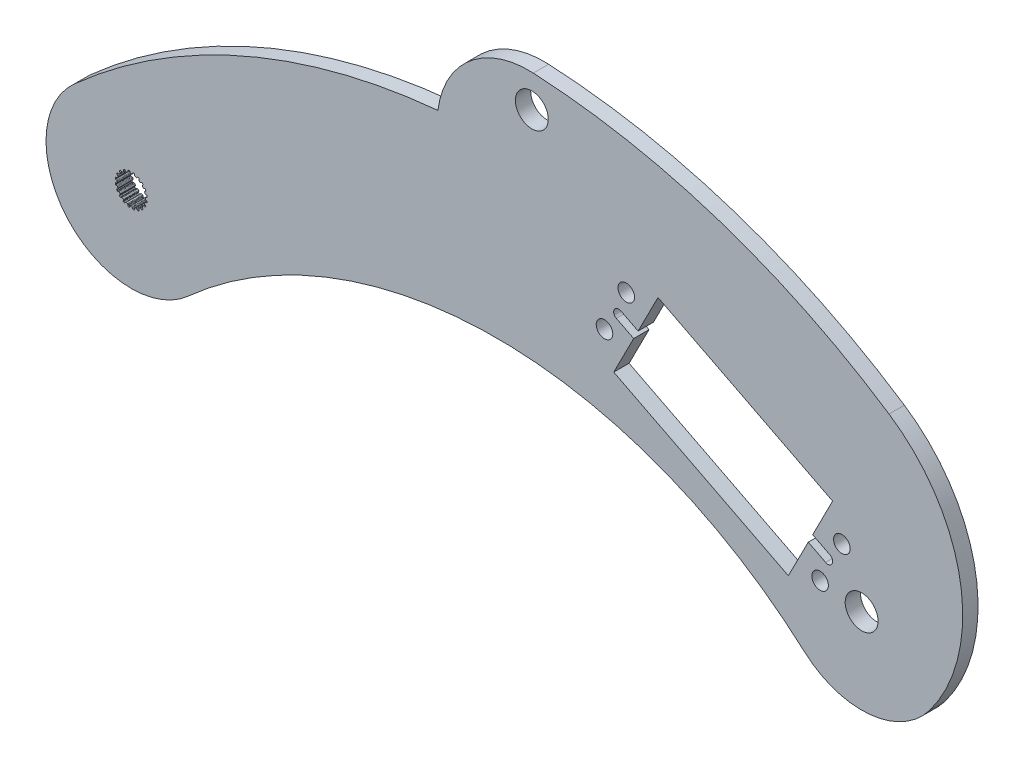
SolidWorks part; units mm, degrees
ref_plane "Front Plane" through (0, 0, 0) normal (0, 0, 1) x (1, 0, 0)
ref_plane "Top Plane" through (0, 0, 0) normal (0, 1, 0) x (1, 0, 0)
ref_plane "Right Plane" through (0, 0, 0) normal (1, 0, 0) x (0, 0, -1)
sketch "Sketch1" plane through (0, 0, 0) normal (0, 0, 1) x (1, 0, 0)
  line L0 (-0.1069, 2.9699) -> (0.1069, 2.9699)
  line L1 (0.3159, 3.2375) -> (0.2537, 3.0575)
  line L2 (-0.2964, 3.2367) -> (-0.2318, 3.0575)
  line L3 (-0.2964, 3.2367) -> (0.3159, 3.2375) construction
  line L4 (0, 3.3252) -> (0, 0) construction
  line L5 (-0.2318, 3.0575) -> (0.2537, 3.0575) construction
  line L6 (-0.4281, 3.3241) -> (0.4281, 3.3263) construction
  line L7 (0.7183, 3.1698) -> (0.7244, 2.9795)
  line L8 (0.816, 2.8576) -> (1.0195, 2.7915)
  line L9 (1.3009, 2.9815) -> (1.1862, 2.8295)
  line L10 (1.6627, 2.7927) -> (1.6097, 2.6099)
  line L11 (1.6591, 2.4655) -> (1.8322, 2.3398)
  line L12 (2.1585, 2.4335) -> (2.0025, 2.3245)
  line L13 (2.4443, 2.1423) -> (2.3374, 1.9847)
  line L14 (2.3398, 1.8322) -> (2.4655, 1.6591)
  line L15 (2.8049, 1.6474) -> (2.6228, 1.5919)
  line L16 (2.9866, 1.2821) -> (2.8363, 1.1653)
  line L17 (2.7915, 1.0195) -> (2.8576, 0.816)
  line L18 (3.1767, 0.7) -> (2.9863, 0.7035)
  line L19 (3.2367, 0.2964) -> (3.0575, 0.2318)
  line L20 (2.9699, 0.1069) -> (2.9699, -0.1069)
  line L21 (3.2375, -0.3159) -> (3.0575, -0.2537)
  line L22 (3.1698, -0.7183) -> (2.9795, -0.7244)
  line L23 (2.8576, -0.816) -> (2.7915, -1.0195)
  line L24 (2.9815, -1.3009) -> (2.8295, -1.1862)
  line L25 (2.7927, -1.6627) -> (2.6099, -1.6097)
  line L26 (2.4655, -1.6591) -> (2.3398, -1.8322)
  line L27 (2.4335, -2.1585) -> (2.3245, -2.0025)
  line L28 (2.1423, -2.4443) -> (1.9847, -2.3374)
  line L29 (1.8322, -2.3398) -> (1.6591, -2.4655)
  line L30 (1.6474, -2.8049) -> (1.5919, -2.6228)
  line L31 (1.2821, -2.9866) -> (1.1653, -2.8363)
  line L32 (1.0195, -2.7915) -> (0.816, -2.8576)
  line L33 (0.7, -3.1767) -> (0.7035, -2.9863)
  line L34 (0.2964, -3.2367) -> (0.2318, -3.0575)
  line L35 (0.1069, -2.9699) -> (-0.1069, -2.9699)
  line L36 (-0.3159, -3.2375) -> (-0.2537, -3.0575)
  line L37 (-0.7183, -3.1698) -> (-0.7244, -2.9795)
  line L38 (-0.816, -2.8576) -> (-1.0195, -2.7915)
  line L39 (-1.3009, -2.9815) -> (-1.1862, -2.8295)
  line L40 (-1.6627, -2.7927) -> (-1.6097, -2.6099)
  line L41 (-1.6591, -2.4655) -> (-1.8322, -2.3398)
  line L42 (-2.1585, -2.4335) -> (-2.0025, -2.3245)
  line L43 (-2.4443, -2.1423) -> (-2.3374, -1.9847)
  line L44 (-2.3398, -1.8322) -> (-2.4655, -1.6591)
  line L45 (-2.8049, -1.6474) -> (-2.6228, -1.5919)
  line L46 (-2.9866, -1.2821) -> (-2.8363, -1.1653)
  line L47 (-2.7915, -1.0195) -> (-2.8576, -0.816)
  line L48 (-3.1767, -0.7) -> (-2.9863, -0.7035)
  line L49 (-3.2367, -0.2964) -> (-3.0575, -0.2318)
  line L50 (-2.9699, -0.1069) -> (-2.9699, 0.1069)
  line L51 (-3.2375, 0.3159) -> (-3.0575, 0.2537)
  line L52 (-3.1698, 0.7183) -> (-2.9795, 0.7244)
  line L53 (-2.8576, 0.816) -> (-2.7915, 1.0195)
  line L54 (-2.9815, 1.3009) -> (-2.8295, 1.1862)
  line L55 (-2.7927, 1.6627) -> (-2.6099, 1.6097)
  line L56 (-2.4655, 1.6591) -> (-2.3398, 1.8322)
  line L57 (-2.4335, 2.1585) -> (-2.3245, 2.0025)
  line L58 (-2.1423, 2.4443) -> (-1.9847, 2.3374)
  line L59 (-1.8322, 2.3398) -> (-1.6591, 2.4655)
  line L60 (-1.6474, 2.8049) -> (-1.5919, 2.6228)
  line L61 (-1.2821, 2.9866) -> (-1.1653, 2.8363)
  line L62 (-1.0195, 2.7915) -> (-0.816, 2.8576)
  line L63 (-0.7, 3.1767) -> (-0.7035, 2.9863)
  line L64 (0.4281, 3.3263) -> (0.62, 3.2938)
  line L65 (1.4351, 3.0312) -> (1.6075, 2.9409)
  line L66 (2.3015, 2.4394) -> (2.4376, 2.3003)
  line L67 (2.9427, 1.6088) -> (3.0291, 1.4344)
  line L68 (3.2958, 0.6207) -> (3.3241, 0.4281)
  line L69 (3.3263, -0.4281) -> (3.2938, -0.62)
  line L70 (3.0312, -1.4351) -> (2.9409, -1.6075)
  line L71 (2.4394, -2.3015) -> (2.3003, -2.4376)
  line L72 (1.6088, -2.9427) -> (1.4344, -3.0291)
  line L73 (0.6207, -3.2958) -> (0.4281, -3.3241)
  line L74 (-0.4281, -3.3263) -> (-0.62, -3.2938)
  line L75 (-1.4351, -3.0312) -> (-1.6075, -2.9409)
  line L76 (-2.3015, -2.4394) -> (-2.4376, -2.3003)
  line L77 (-2.9427, -1.6088) -> (-3.0291, -1.4344)
  line L78 (-3.2958, -0.6207) -> (-3.3241, -0.4281)
  line L79 (-3.3263, 0.4281) -> (-3.2938, 0.62)
  line L80 (-3.0312, 1.4351) -> (-2.9409, 1.6075)
  line L81 (-2.4394, 2.3015) -> (-2.3003, 2.4376)
  line L82 (-1.6088, 2.9427) -> (-1.4344, 3.0291)
  line L83 (-0.6207, 3.2958) -> (-0.4281, 3.3241)
  line L84 (-11.8753, 13.2369) -> (11.8753, -13.2369) construction
  line L85 (164.2753, 13.2369) -> (140.5247, -13.2369) construction
  line L86 (0, 0) -> (152.4, 0) construction
  arc A0 (0.2537, 3.0575) -> (0.1069, 2.9699) centre (0.1283, 3.1009) cw
  arc A1 (-0.2318, 3.0575) -> (-0.1069, 2.9699) centre (-0.1069, 3.1026) ccw
  arc A2 (0.62, 3.2938) -> (0.7183, 3.1698) centre (0.5856, 3.1656) cw
  arc A3 (0.7244, 2.9795) -> (0.816, 2.8576) centre (0.857, 2.9838) ccw
  arc A4 (-0.4281, 3.3241) -> (-0.2964, 3.2367) centre (-0.4213, 3.1916) cw
  arc A5 (0.4281, 3.3263) -> (0.3159, 3.2375) centre (0.4413, 3.1942) ccw
  arc A6 (1.1862, 2.8295) -> (1.0195, 2.7915) centre (1.0802, 2.9095) cw
  arc A7 (1.4351, 3.0312) -> (1.3009, 2.9815) centre (1.4068, 2.9015) ccw
  arc A8 (1.6075, 2.9409) -> (1.6627, 2.7927) centre (1.5352, 2.8297) cw
  arc A9 (1.6097, 2.6099) -> (1.6591, 2.4655) centre (1.7371, 2.5729) ccw
  arc A10 (2.0025, 2.3245) -> (1.8322, 2.3398) centre (1.9264, 2.4332) cw
  arc A11 (2.3015, 2.4394) -> (2.1585, 2.4335) centre (2.2346, 2.3248) ccw
  arc A12 (2.4376, 2.3003) -> (2.4443, 2.1423) centre (2.3345, 2.2168) cw
  arc A13 (2.3374, 1.9847) -> (2.3398, 1.8322) centre (2.4472, 1.9102) ccw
  arc A14 (2.6228, 1.5919) -> (2.4655, 1.6591) centre (2.5841, 1.7189) cw
  arc A15 (2.9427, 1.6088) -> (2.8049, 1.6474) centre (2.8436, 1.5205) ccw
  arc A16 (3.0291, 1.4344) -> (2.9866, 1.2821) centre (2.9052, 1.3869) cw
  arc A17 (2.8363, 1.1653) -> (2.7915, 1.0195) centre (2.9177, 1.0605) ccw
  arc A18 (2.9863, 0.7035) -> (2.8576, 0.816) centre (2.9887, 0.8362) cw
  arc A19 (3.2958, 0.6207) -> (3.1767, 0.7) centre (3.1743, 0.5673) ccw
  arc A20 (3.3241, 0.4281) -> (3.2367, 0.2964) centre (3.1916, 0.4213) cw
  arc A21 (3.0575, 0.2318) -> (2.9699, 0.1069) centre (3.1026, 0.1069) ccw
  arc A22 (3.0575, -0.2537) -> (2.9699, -0.1069) centre (3.1009, -0.1283) cw
  arc A23 (3.3263, -0.4281) -> (3.2375, -0.3159) centre (3.1942, -0.4413) ccw
  arc A24 (3.2938, -0.62) -> (3.1698, -0.7183) centre (3.1656, -0.5856) cw
  arc A25 (2.9795, -0.7244) -> (2.8576, -0.816) centre (2.9838, -0.857) ccw
  arc A26 (2.8295, -1.1862) -> (2.7915, -1.0195) centre (2.9095, -1.0802) cw
  arc A27 (3.0312, -1.4351) -> (2.9815, -1.3009) centre (2.9015, -1.4068) ccw
  arc A28 (2.9409, -1.6075) -> (2.7927, -1.6627) centre (2.8297, -1.5352) cw
  arc A29 (2.6099, -1.6097) -> (2.4655, -1.6591) centre (2.5729, -1.7371) ccw
  arc A30 (2.3245, -2.0025) -> (2.3398, -1.8322) centre (2.4332, -1.9264) cw
  arc A31 (2.4394, -2.3015) -> (2.4335, -2.1585) centre (2.3248, -2.2346) ccw
  arc A32 (2.3003, -2.4376) -> (2.1423, -2.4443) centre (2.2168, -2.3345) cw
  arc A33 (1.9847, -2.3374) -> (1.8322, -2.3398) centre (1.9102, -2.4472) ccw
  arc A34 (1.5919, -2.6228) -> (1.6591, -2.4655) centre (1.7189, -2.5841) cw
  arc A35 (1.6088, -2.9427) -> (1.6474, -2.8049) centre (1.5205, -2.8436) ccw
  arc A36 (1.4344, -3.0291) -> (1.2821, -2.9866) centre (1.3869, -2.9052) cw
  arc A37 (1.1653, -2.8363) -> (1.0195, -2.7915) centre (1.0605, -2.9177) ccw
  arc A38 (0.7035, -2.9863) -> (0.816, -2.8576) centre (0.8362, -2.9887) cw
  arc A39 (0.6207, -3.2958) -> (0.7, -3.1767) centre (0.5673, -3.1743) ccw
  arc A40 (0.4281, -3.3241) -> (0.2964, -3.2367) centre (0.4213, -3.1916) cw
  arc A41 (0.2318, -3.0575) -> (0.1069, -2.9699) centre (0.1069, -3.1026) ccw
  arc A42 (-0.2537, -3.0575) -> (-0.1069, -2.9699) centre (-0.1283, -3.1009) cw
  arc A43 (-0.4281, -3.3263) -> (-0.3159, -3.2375) centre (-0.4413, -3.1942) ccw
  arc A44 (-0.62, -3.2938) -> (-0.7183, -3.1698) centre (-0.5856, -3.1656) cw
  arc A45 (-0.7244, -2.9795) -> (-0.816, -2.8576) centre (-0.857, -2.9838) ccw
  arc A46 (-1.1862, -2.8295) -> (-1.0195, -2.7915) centre (-1.0802, -2.9095) cw
  arc A47 (-1.4351, -3.0312) -> (-1.3009, -2.9815) centre (-1.4068, -2.9015) ccw
  arc A48 (-1.6075, -2.9409) -> (-1.6627, -2.7927) centre (-1.5352, -2.8297) cw
  arc A49 (-1.6097, -2.6099) -> (-1.6591, -2.4655) centre (-1.7371, -2.5729) ccw
  arc A50 (-2.0025, -2.3245) -> (-1.8322, -2.3398) centre (-1.9264, -2.4332) cw
  arc A51 (-2.3015, -2.4394) -> (-2.1585, -2.4335) centre (-2.2346, -2.3248) ccw
  arc A52 (-2.4376, -2.3003) -> (-2.4443, -2.1423) centre (-2.3345, -2.2168) cw
  arc A53 (-2.3374, -1.9847) -> (-2.3398, -1.8322) centre (-2.4472, -1.9102) ccw
  arc A54 (-2.6228, -1.5919) -> (-2.4655, -1.6591) centre (-2.5841, -1.7189) cw
  arc A55 (-2.9427, -1.6088) -> (-2.8049, -1.6474) centre (-2.8436, -1.5205) ccw
  arc A56 (-3.0291, -1.4344) -> (-2.9866, -1.2821) centre (-2.9052, -1.3869) cw
  arc A57 (-2.8363, -1.1653) -> (-2.7915, -1.0195) centre (-2.9177, -1.0605) ccw
  arc A58 (-2.9863, -0.7035) -> (-2.8576, -0.816) centre (-2.9887, -0.8362) cw
  arc A59 (-3.2958, -0.6207) -> (-3.1767, -0.7) centre (-3.1743, -0.5673) ccw
  arc A60 (-3.3241, -0.4281) -> (-3.2367, -0.2964) centre (-3.1916, -0.4213) cw
  arc A61 (-3.0575, -0.2318) -> (-2.9699, -0.1069) centre (-3.1026, -0.1069) ccw
  arc A62 (-3.0575, 0.2537) -> (-2.9699, 0.1069) centre (-3.1009, 0.1283) cw
  arc A63 (-3.3263, 0.4281) -> (-3.2375, 0.3159) centre (-3.1942, 0.4413) ccw
  arc A64 (-3.2938, 0.62) -> (-3.1698, 0.7183) centre (-3.1656, 0.5856) cw
  arc A65 (-2.9795, 0.7244) -> (-2.8576, 0.816) centre (-2.9838, 0.857) ccw
  arc A66 (-2.8295, 1.1862) -> (-2.7915, 1.0195) centre (-2.9095, 1.0802) cw
  arc A67 (-3.0312, 1.4351) -> (-2.9815, 1.3009) centre (-2.9015, 1.4068) ccw
  arc A68 (-2.9409, 1.6075) -> (-2.7927, 1.6627) centre (-2.8297, 1.5352) cw
  arc A69 (-2.6099, 1.6097) -> (-2.4655, 1.6591) centre (-2.5729, 1.7371) ccw
  arc A70 (-2.3245, 2.0025) -> (-2.3398, 1.8322) centre (-2.4332, 1.9264) cw
  arc A71 (-2.4394, 2.3015) -> (-2.4335, 2.1585) centre (-2.3248, 2.2346) ccw
  arc A72 (-2.3003, 2.4376) -> (-2.1423, 2.4443) centre (-2.2168, 2.3345) cw
  arc A73 (-1.9847, 2.3374) -> (-1.8322, 2.3398) centre (-1.9102, 2.4472) ccw
  arc A74 (-1.5919, 2.6228) -> (-1.6591, 2.4655) centre (-1.7189, 2.5841) cw
  arc A75 (-1.6088, 2.9427) -> (-1.6474, 2.8049) centre (-1.5205, 2.8436) ccw
  arc A76 (-1.4344, 3.0291) -> (-1.2821, 2.9866) centre (-1.3869, 2.9052) cw
  arc A77 (-1.1653, 2.8363) -> (-1.0195, 2.7915) centre (-1.0605, 2.9177) ccw
  arc A78 (-0.7035, 2.9863) -> (-0.816, 2.8576) centre (-0.8362, 2.9887) cw
  arc A79 (-0.6207, 3.2958) -> (-0.7, 3.1767) centre (-0.5673, 3.1743) ccw
  circle A80 centre (0, 0) radius 12.7 construction
  arc A81 (-11.8753, 13.2369) -> (164.2753, 13.2369) centre (76.2, -84.9368) cw
  arc A82 (11.8753, -13.2369) -> (140.5247, -13.2369) centre (76.2, -84.9368) cw
  arc A84 (-11.8753, 13.2369) -> (11.8753, -13.2369) centre (0, 0) ccw
  arc A85 (164.2753, 13.2369) -> (140.5247, -13.2369) centre (152.4, 0) cw
  point P14 (0, 2.9699)
  point P26 (0, 0)
  point P247 (0, 0)
  dimension "D4" = 0.1327
  dimension "D8" = 20
  dimension "D9" = 25.4
  dimension "D10" = 131.8914
  dimension "D1" = 2.9699
  dimension "D2" = 0.2139
  dimension "D3" = 0.1904
  dimension "D5" = 0.0877
  dimension "D6" = 0.4855
  dimension "D7" = 0.8563
  dimension "D11" = 35.5662
  dimension "D12" = 152.4
extrude "Boss-Extrude1" add sketch "Sketch1" along normal blind 3.2004
sketch "Sketch2" plane through (0, 0, 3.2004) normal (0, 0, 1) x (1, 0, 0)
  line L0 (132.2879, 12.7254) -> (132.9641, 14.0508) construction
  line L5 (128.1311, 26.252) -> (118.8966, 8.1515) construction
  line L7 (109.9175, 35.5442) -> (146.3447, 16.9598)
  line L13 (109.9175, 35.5442) -> (100.683, 17.4437)
  line L19 (98.7496, 24.2228) -> (103.2942, 33.1305) construction
  line L20 (143.7335, 1.273) -> (148.2781, 10.1807) construction
  line L24 (101.0219, 28.6767) -> (146.0058, 5.7268) construction
  line L30 (100.683, 17.4437) -> (137.1102, -1.1407)
  line L31 (146.3447, 16.9598) -> (137.1102, -1.1407)
  circle A7 centre (103.2942, 33.1305) radius 1.7272
  circle A9 centre (143.7335, 1.273) radius 1.7272
  circle A10 centre (148.2781, 10.1807) radius 1.7272
  circle A11 centre (98.7496, 24.2228) radius 1.7272
  circle A13 centre (132.2879, 12.7254) radius 3.429 construction
  arc A14 (0, 0) -> (152.4, 0) centre (76.2, -84.9368) cw construction
  arc A15 (-11.8753, 13.2369) -> (11.8753, -13.2369) centre (0, 0) ccw construction
  arc A16 (140.5247, -13.2369) -> (164.2753, 13.2369) centre (152.4, 0) ccw construction
  arc A17 (164.2753, 13.2369) -> (-11.8753, 13.2369) centre (76.2, -84.9368) ccw construction
  circle A18 centre (152.4, 0) radius 3.429
  point P0 (132.2879, 12.7254)
  point P1 (99.9946, 26.663)
  point P24 (123.5139, 17.2018)
  dimension "D2" = 15.4
  dimension "D3" = 6.858
  dimension "D5" = 3.4544
  dimension "D10" = 6.858
  dimension "D6" = 2.2606
  dimension "D8" = 20.32
  dimension "D13" = 23.7998
  dimension "D1" = 50.5
  dimension "D4" = 10
  dimension "D7" = 1.4879
  dimension "D9" = 40.894
extrude "Cut-Extrude1" cut sketch "Sketch2" against normal up to surface (3.2004 mm away) up to face at (76.2, 8.6481, 0)
sketch "Sketch3" plane through (0, 0, 3.2004) normal (0, 0, 1) x (1, 0, 0)
  line L0 (146.3447, 16.9598) -> (137.1102, -1.1407) construction
  line L1 (109.9175, 35.5442) -> (100.683, 17.4437) construction
  line L4 (102.1419, 29.2459) -> (105.762, 27.399)
  line L5 (102.1419, 29.2459) -> (101.2184, 27.4358) construction
  line L7 (101.2184, 27.4358) -> (104.8385, 25.5889)
  line L8 (105.762, 27.399) -> (104.8385, 25.5889)
  line L9 (142.1892, 8.8146) -> (145.8093, 6.9677)
  line L10 (142.1892, 8.8146) -> (141.2657, 7.0045)
  line L11 (141.2657, 7.0045) -> (144.8858, 5.1576)
  line L12 (145.8093, 6.9677) -> (144.8858, 5.1576) construction
  arc A6 (145.8093, 6.9677) -> (144.8858, 5.1576) centre (145.3475, 6.0627) cw
  arc A7 (102.1419, 29.2459) -> (101.2184, 27.4358) centre (101.6802, 28.3409) ccw
  point P22 (105.3003, 26.494)
  point P23 (141.7274, 7.9096)
  dimension "D4" = 4.064
  dimension "D5" = 2.032
extrude "Cut-Extrude2" cut sketch "Sketch3" against normal up to surface (3.2004 mm away) up to face at (97.0224, 24.2228, 0)
sketch "Sketch4" plane through (0, 0, 3.2004) normal (0, 0, 1) x (1, 0, 0)
  line L1 (83.5881, 56.2861) -> (152.4, 0) construction
  line L2 (83.5881, 56.2861) -> (83.1655, 46.7705) construction
  line L4 (158.1231, 38.5869) -> (166.6312, -10.6636) construction
  line L5 (83.89, 63.0847) -> (63.9945, 46.3886) construction
  arc A0 (63.9945, 46.3886) -> (83.89, 63.0847) centre (82.9016, 44.0604) cw
  arc A1 (164.2753, 13.2369) -> (-11.8753, 13.2369) centre (76.2, -84.9368) ccw construction
  circle A3 centre (152.4, 0) radius 3.429 construction
  circle A4 centre (83.5881, 56.2861) radius 3.429
  circle A5 centre (152.4, 0) radius 3.429 construction
  arc A6 (83.89, 63.0847) -> (158.1231, 38.5869) centre (76.2, -84.9368) cw
  arc A7 (166.6312, -10.6636) -> (164.2753, 13.2369) centre (152.4, 0) ccw
  arc A8 (164.2753, 13.2369) -> (63.9945, 46.3886) centre (76.2, -84.9368) ccw
  arc A9 (164.2753, 13.2369) -> (-11.8753, 13.2369) centre (76.2, -84.9368) ccw construction
  arc A10 (158.1231, 38.5869) -> (166.6312, -10.6636) centre (139.1275, 9.9453) cw
  arc A11 (140.5247, -13.2369) -> (164.2753, 13.2369) centre (152.4, 0) ccw construction
  dimension "D4" = 49.98
  dimension "D3" = 19.05
  dimension "D1" = 9.525
  dimension "D2" = 88.9
  dimension "D5" = 25.9729
  dimension "D6" = 53.261
extrude "Boss-Extrude2" add sketch "Sketch4" against normal up to surface (3.2004 mm away) up to face at (123.5139, 17.2018, 0)
